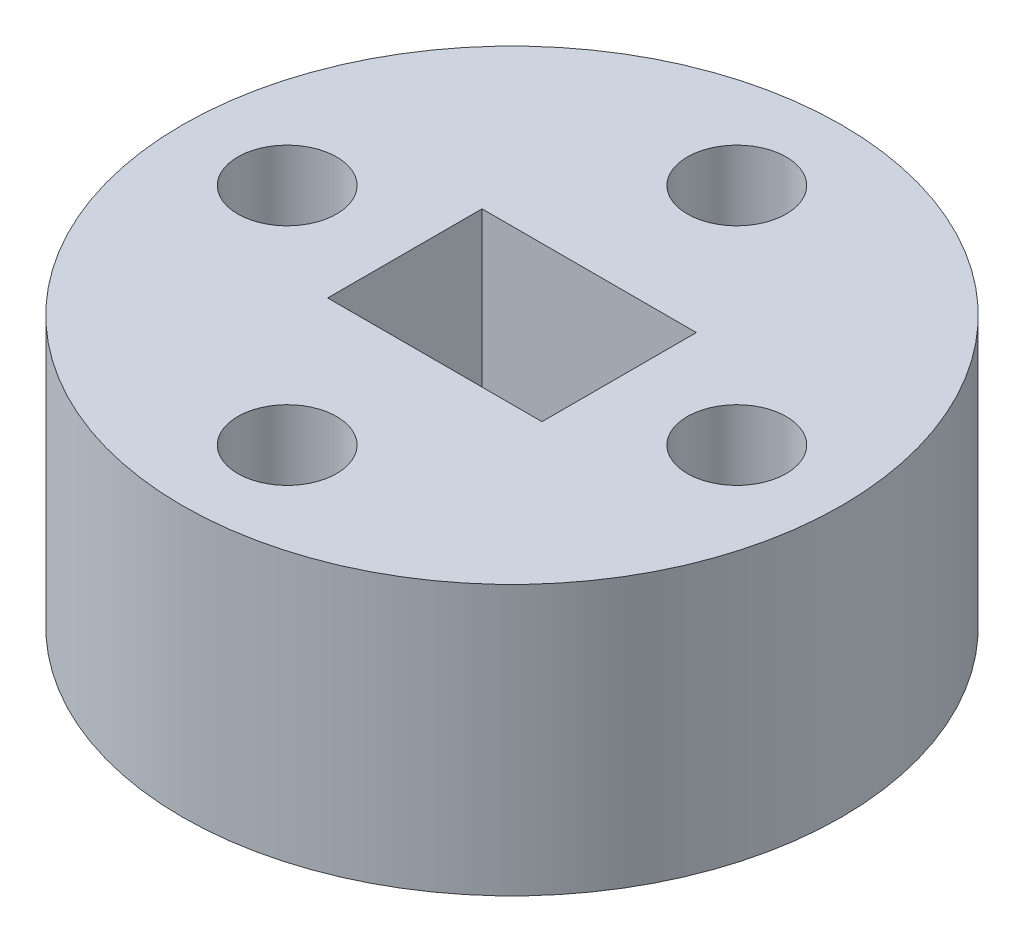
SolidWorks part; units mm, degrees
ref_plane "Front Plane" through (0, 0, 0) normal (0, 0, 1) x (1, 0, 0)
ref_plane "Top Plane" through (0, 0, 0) normal (0, 1, 0) x (1, 0, 0)
ref_plane "Right Plane" through (0, 0, 0) normal (1, 0, 0) x (0, 0, -1)
sketch "Sketch1" plane through (0, 0, 0) normal (0, 1, 0) x (1, 0, 0)
  line L1 (-7.15, -5.15) -> (7.15, -5.15)
  line L2 (-7.15, -5.15) -> (-7.15, 5.15)
  line L3 (-7.15, 5.15) -> (7.15, 5.15)
  line L4 (7.15, -5.15) -> (7.15, 5.15)
  circle A0 centre (0, 0) radius 22
  circle A1 centre (-15, 0) radius 3.3
  circle A2 centre (15, 0) radius 3.3
  circle A3 centre (0, -15) radius 3.3
  circle A4 centre (0, 15) radius 3.3
extrude "Stem_Adapter_Flange" add sketch "Sketch1" along normal blind 18
equation "\"ValveDiameter\" = 50mm"
equation "\"MotorGearTeeth\" = 40"
equation "\"OutputGearTeeth\" = 80"
equation "\"GearModule\" = 1.5mm"
equation "\"PressureAngle\" = 20deg"
equation "\"GearCenterDistance\" = 90mm"
equation "\"GearWidth\" = 18mm"
equation "\"OutputShaftDiameter\" = 20mm"
equation "\"BearingOD\" = 47mm"
equation "\"BearingWidth\" = 14mm"
equation "\"PlateThickness\" = 6mm"
equation "\"ValveRotation\" = 90deg"
